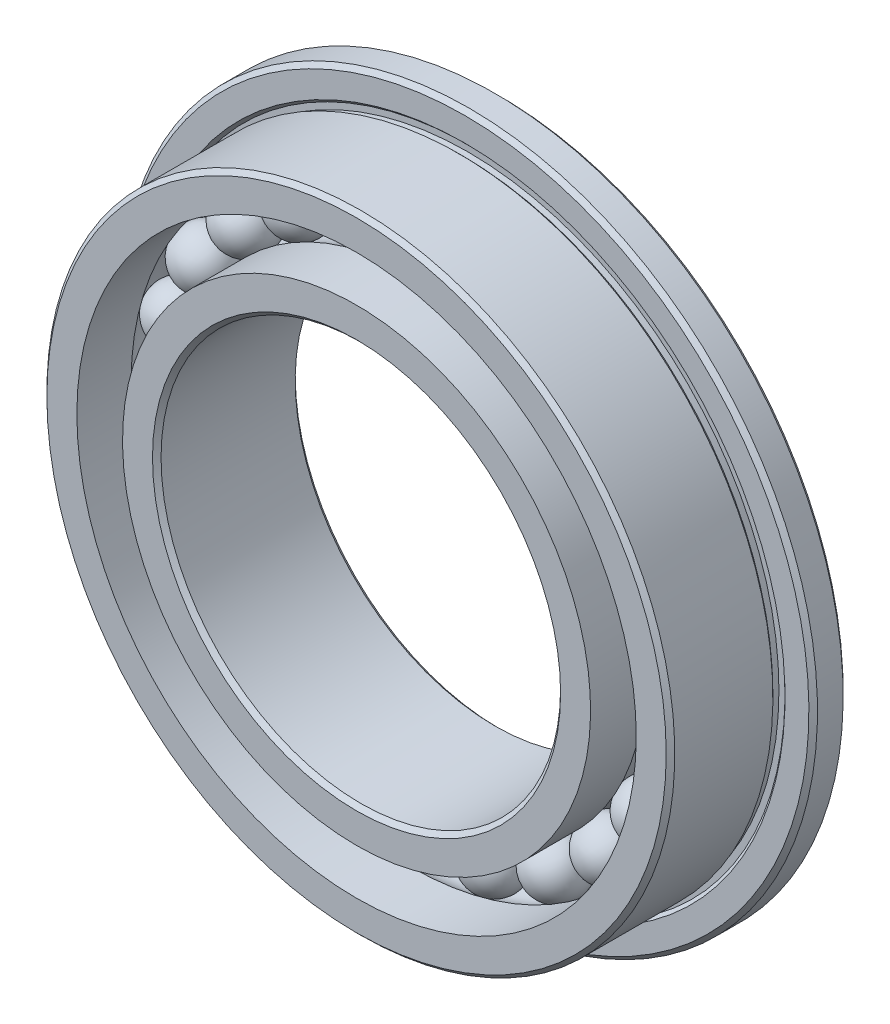
SolidWorks part; units mm, degrees
material "AISI 1020"
ref_plane "Front Plane" through (0, 0, 0) normal (0, 0, 1) x (1, 0, 0)
ref_plane "Top Plane" through (0, 0, 0) normal (0, 1, 0) x (1, 0, 0)
ref_plane "Right Plane" through (0, 0, 0) normal (1, 0, 0) x (0, 0, -1)
sketch "Sketch1" plane through (0, 0, 0) normal (1, 0, 0) x (0, 0, -1)
  line L0 (0, 5.5) -> (0, -5.5) construction
  line L1 (-1.25, 5.5) -> (1.25, 5.5) construction
  line L2 (0, 0) -> (1.25, 0) construction
  line L3 (1.25, 6.1) -> (1.25, -6.1) construction
  line L4 (1.25, -6.1) -> (0.65, -6.1) construction
  line L5 (1.25, 3.5) -> (0, 3.5) construction
  line L6 (1.25, 3.5) -> (1.25, -3.5) construction
  dimension "OD" = 11
  dimension "Width" = 2.5
  dimension "Flange Thickness" = 0.6
  dimension "ID" = 7
  dimension "Flange OD" = 12.2
sketch "Sketch2" plane through (0, 0, 0) normal (1, 0, 0) x (0, 0, -1)
  line L0 (1.25, 6.1) -> (0.65, 6.1)
  line L1 (0.65, 6.1) -> (0.65, 5.6061)
  line L2 (0.5439, 5.5) -> (-1.25, 5.5)
  line L3 (-1.25, 5.5) -> (-1.25, 4.9)
  line L4 (-1.25, 4.9) -> (-0.3, 4.9)
  line L5 (1.25, 6.1) -> (1.25, -6.1) construction
  line L6 (1.25, 4.9) -> (1.25, 6.1)
  line L7 (1.25, 3.5) -> (-1.25, 3.5)
  line L8 (-1.25, 3.5) -> (-1.25, 4.1)
  line L9 (-1.25, 4.1) -> (-0.3, 4.1)
  line L10 (1.25, 4.1) -> (1.25, 3.5)
  line L11 (0, 5.5) -> (0, 3.5) construction
  line L12 (-0.5, 4.5) -> (0.5, 4.5) construction
  line L13 (0.3, 4.9) -> (1.25, 4.9)
  line L14 (0.3, 4.1) -> (1.25, 4.1)
  line L15 (0.65, 5.6061) -> (0.703, 5.553)
  line L16 (0.703, 5.553) -> (0.703, 5.447)
  line L17 (0.703, 5.447) -> (0.597, 5.447)
  line L18 (0.597, 5.447) -> (0.5439, 5.5)
  line L19 (0.65, 5.5) -> (0.703, 5.447) construction
  line L20 (0.703, 5.553) -> (0.597, 5.447) construction
  line L21 (0.5439, 5.5) -> (0.65, 5.5) construction
  line L22 (0.65, 5.5) -> (0.65, 5.6061) construction
  circle A0 centre (0, 4.5) radius 0.5 construction
  arc A1 (-0.3, 4.9) -> (0.3, 4.9) centre (0, 4.5) cw
  arc A2 (-0.3, 4.1) -> (0.3, 4.1) centre (0, 4.5) ccw
  dimension "D1" = 2
  dimension "Ball Dia." = 1
  dimension "D2" = 135
  dimension "D3" = 0.15
  dimension "D4" = 0.8
  dimension "Race Thikness" = 0.6
revolve "Revolve1" add sketch "Sketch2" angle 360 about L2
fillet "Fillet1" radius 0.075 3 edges at (0, -6.1, -1.25) (0, -6.1, -0.65) (0, -5.5, 1.25) profile chamfer
sketch "Sketch3" plane through (0, 0, 0) normal (0, 0, 1) x (1, 0, 0)
  line L0 (-3.5, 0) -> (3.5, 0) construction
  line L1 (-5.5, 0) -> (5.5, 0) construction
  point P5 (0, 0)
  dimension "ID2" = 7
  dimension "OD2" = 11
fillet "Fillet2" radius 0.075 2 edges at (0, -3.5, -1.25) (0, -3.5, 1.25) profile chamfer
sketch "Sketch7" plane through (0, 0, 0) normal (0, 0, 1) x (1, 0, 0)
  line L0 (0, 5) -> (0, 4)
  line L1 (0, 6.1) -> (0, -6.1) construction
  line L2 (-0.559, 5) -> (0, 0) construction
  line L3 (0, 0) -> (0.559, 5) construction
  line L4 (0.559, 5) -> (-0.559, 5) construction
  circle A0 centre (0, 4.5) radius 0.5 construction
  circle A1 centre (0, 0) radius 5 construction
  circle A2 centre (0, 0) radius 4 construction
  arc A4 (0, 5) -> (0, 4) centre (0, 4.5) ccw
  dimension "D1" = 12.759
revolve "Revolve3" add sketch "Sketch7" angle 360 about L0
pattern_circular "CirPattern3" count 24 over 360 about axis through (0, 0, 0) along (0, 0, 1) of bodies 107
sketch "Sketch8" plane through (0, 0, 0) normal (1, 0, 0) x (0, 0, -1)
  line L0 (-1.25, 5.5) -> (1.25, 5.5) construction
  line L1 (1.25, 5.5) -> (1.25, 6.1) construction
  line L2 (-1.25, -5.5) -> (1.25, -5.5) construction
  line L3 (1.25, 6.1) -> (1.25, -6.1) construction
  dimension "D1" = 11
equation "\"Ball Dia.@Sketch2\" = ( \"OD@Sketch1\" - \"ID@Sketch1\" ) * .25"
equation "\"D3@Sketch2\"=\"Flange Thickness@Sketch1\"/4"
equation "\"D1@Fillet1\" = \"Race Thikness@Sketch2\" / 8"
equation "\"ID2@Sketch3\" = \"ID@Sketch1\""
equation "\"OD2@Sketch3\" = \"OD@Sketch1\""
equation "\"D1@Fillet2\" = \"Race Thikness@Sketch2\" / 8"
equation "\"D1@CirPattern3\"=360/\"D1@Sketch7\"-4"
equation "\"D4@Sketch2\" = ( \"OD@Sketch1\" - \"ID@Sketch1\" ) * .2"
